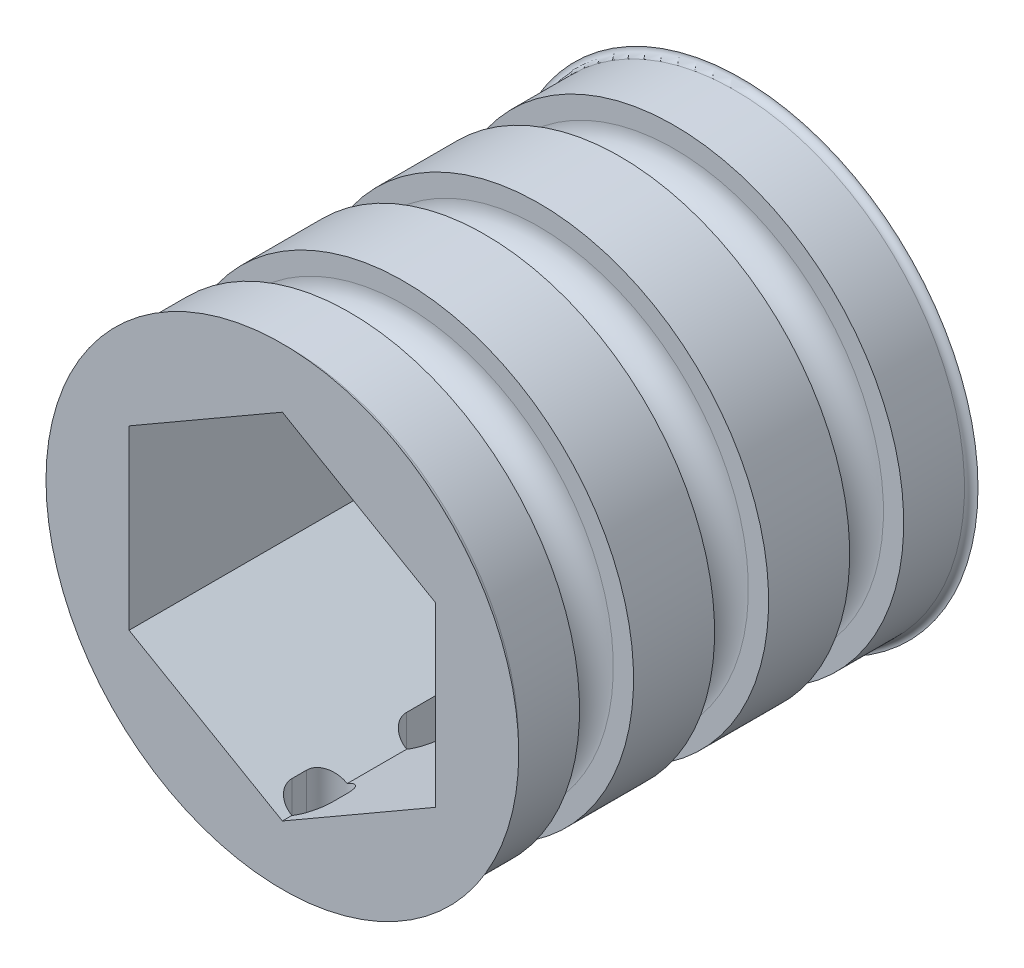
SolidWorks part; units mm, degrees
ref_plane "Plan de face" through (0, 0, 0) normal (0, 0, 1) x (1, 0, 0)
ref_plane "Plan de dessus" through (0, 0, 0) normal (0, 1, 0) x (1, 0, 0)
ref_plane "Plan de droite" through (0, 0, 0) normal (1, 0, 0) x (0, 0, -1)
sketch "Esquisse1" plane through (0, 0, 0) normal (0, 0, 1) x (1, 0, 0)
  circle A0 centre (0, 0) radius 3.25
  circle A1 centre (0, 0) radius 18
  dimension "D1" = 36
  dimension "D2" = 6.5
extrude "Boss.-Extru.1" add sketch "Esquisse1" along normal blind 34
sketch "Esquisse9" plane through (0, 0, 34) normal (0, 0, 1) x (1, 0, 0)
  line L0 (0, 0) -> (0, 26.2117) construction
  line L1 (11.35, -6.5529) -> (11.35, 6.5529)
  line L2 (11.35, 6.5529) -> (0, 13.1059)
  line L3 (0, 13.1059) -> (-11.35, 6.5529)
  line L4 (-11.35, 6.5529) -> (-11.35, -6.5529)
  line L5 (-11.35, -6.5529) -> (0, -13.1059)
  line L6 (0, -13.1059) -> (11.35, -6.5529)
  circle A0 centre (0, 0) radius 11.35 construction
  dimension "D1" = 22.7
extrude "Enlèv. mat.-Extru.9" cut sketch "Esquisse9" against normal offset from surface (18 mm away) 16 up to face at (18, 0, 0)
sketch "Esquisse11" plane through (0, 0, 0) normal (0, 0, -1) x (-1, 0, 0)
  circle A1 centre (-6.9282, 4) radius 2.1
  circle A2 centre (6.9282, 4) radius 2.1
  circle A3 centre (0, -8) radius 2.1
  circle A4 centre (0, 0) radius 8 construction
  dimension "D3" = 4.2
  dimension "D4" = 16
extrude "Enlèv. mat.-Extru.10" cut sketch "Esquisse11" against normal through all
sketch "Esquisse12" plane through (0, 0, 0) normal (0, 0, -1) x (-1, 0, 0)
  circle A0 centre (-6.9282, 4) radius 4.25
  circle A1 centre (6.9282, 4) radius 4.25
  circle A2 centre (0, -8) radius 4.25
  dimension "D1" = 8.5
extrude "Enlèv. mat.-Extru.11" cut sketch "Esquisse12" against normal blind 4
sketch "Esquisse13" plane through (0, 0, 0) normal (0, 1, 0) x (1, 0, 0)
  line L0 (-18, -34) -> (-17.5, -34)
  line L1 (-18, -34) -> (18, -34) construction
  line L2 (-17, -33.5) -> (-17, -29)
  line L3 (0, 0) -> (0, -49.3031) construction
  line L4 (-17, -25) -> (-17, -19)
  line L5 (-18, 0) -> (-18, -34) construction
  line L6 (-17, -15) -> (-17, -9)
  line L7 (-18, -17) -> (18, -17) construction
  line L8 (-17, -5) -> (-17, -0.5)
  line L9 (-18, 0) -> (18, 0) construction
  line L10 (-17.5, 0) -> (-18, 0)
  line L11 (-18, 0) -> (-18, -34)
  line L12 (18, -34) -> (18, 0) construction
  line L13 (-15.7, -34) -> (-15.7, 0) construction
  line L14 (-17, -5) -> (-15.5, -5)
  line L15 (-15.5, -9) -> (-17, -9)
  line L16 (-17, -15) -> (-15.5, -15)
  line L17 (-15.5, -19) -> (-17, -19)
  line L18 (-17, -25) -> (-15.5, -25)
  line L19 (-15.5, -29) -> (-17, -29)
  arc A0 (-15.5, -5) -> (-15.5, -9) centre (-15.5, -7) cw
  arc A1 (-15.5, -15) -> (-15.5, -19) centre (-15.5, -17) cw
  arc A2 (-15.5, -25) -> (-15.5, -29) centre (-15.5, -27) cw
  arc A3 (-17.5, -34) -> (-17, -33.5) centre (-17.5, -33.5) ccw
  arc A4 (-17, -0.5) -> (-17.5, 0) centre (-17.5, -0.5) ccw
  point P20 (-17, -34)
  point P23 (-17, 0)
  dimension "D15" = 0.5
  dimension "D2" = 2
  dimension "D3" = 1.5
  dimension "D4" = 10
  dimension "D14" = 1
revolve "Enlèvement de matière-Révolution1" cut sketch "Esquisse13" angle 360 about L3
sketch "Esquisse14" plane through (0, 0, 0) normal (0, 0, -1) x (-1, 0, 0)
  circle A0 centre (0, 0) radius 13.1059
extrude "Enlèv. mat.-Extru.12" cut sketch "Esquisse14" against normal offset from surface (12 mm away) 4 up to face at (-4.8282, 4, 16)
sketch "Esquisse15" plane through (0, 0, 0) normal (0, 1, 0) x (1, 0, 0)
  line L0 (0, -20.7) -> (0, -23.3) construction
  line L1 (1.5, -20.7) -> (1.5, -23.3)
  line L2 (-1.5, -20.7) -> (-1.5, -23.3)
  line L3 (-17.5, -34) -> (17.5, -34) construction
  line L7 (0, -30.7) -> (0, -31.8) construction
  line L8 (1.5, -30.7) -> (1.5, -31.8)
  line L9 (-1.5, -30.7) -> (-1.5, -31.8)
  line L10 (0, -6.51) -> (0, -9.479) construction
  line L11 (1.5, -6.51) -> (1.5, -9.479) construction
  line L12 (-1.5, -6.51) -> (-1.5, -9.479) construction
  line L13 (-3.5804, -29.2) -> (3.3426, -29.2) construction
  line L15 (15.5, -29) -> (-15.5, -29) construction
  line L17 (-3.5804, -33.3) -> (3.3426, -33.3) construction
  line L18 (-17, -33.5) -> (17, -33.5) construction
  line L19 (-3.5804, -24.8) -> (3.3426, -24.8) construction
  line L20 (3.3426, -19.2) -> (-3.5804, -19.2) construction
  line L21 (-15.5, -25) -> (15.5, -25) construction
  line L22 (17, -19) -> (-17, -19) construction
  arc A0 (1.5, -20.7) -> (-1.5, -20.7) centre (0, -20.7) ccw
  arc A1 (-1.5, -23.3) -> (1.5, -23.3) centre (0, -23.3) ccw
  arc A2 (1.5, -30.7) -> (-1.5, -30.7) centre (0, -30.7) ccw
  arc A3 (-1.5, -31.8) -> (1.5, -31.8) centre (0, -31.8) ccw
  arc A4 (1.5, -6.51) -> (-1.5, -6.51) centre (0, -6.51) ccw construction
  arc A5 (-1.5, -9.479) -> (1.5, -9.479) centre (0, -9.479) ccw construction
  point P3 (0, -22)
  point P8 (0, -31.25)
  point P19 (0, -7.9945)
  dimension "D3" = 1.5
  dimension "D2" = 0.2
  dimension "D5" = 0.2
  dimension "D1" = 0.2
  dimension "D4" = 12
  dimension "D6" = 0.2
extrude "Enlèv. mat.-Extru.13" cut sketch "Esquisse15" against normal through all
